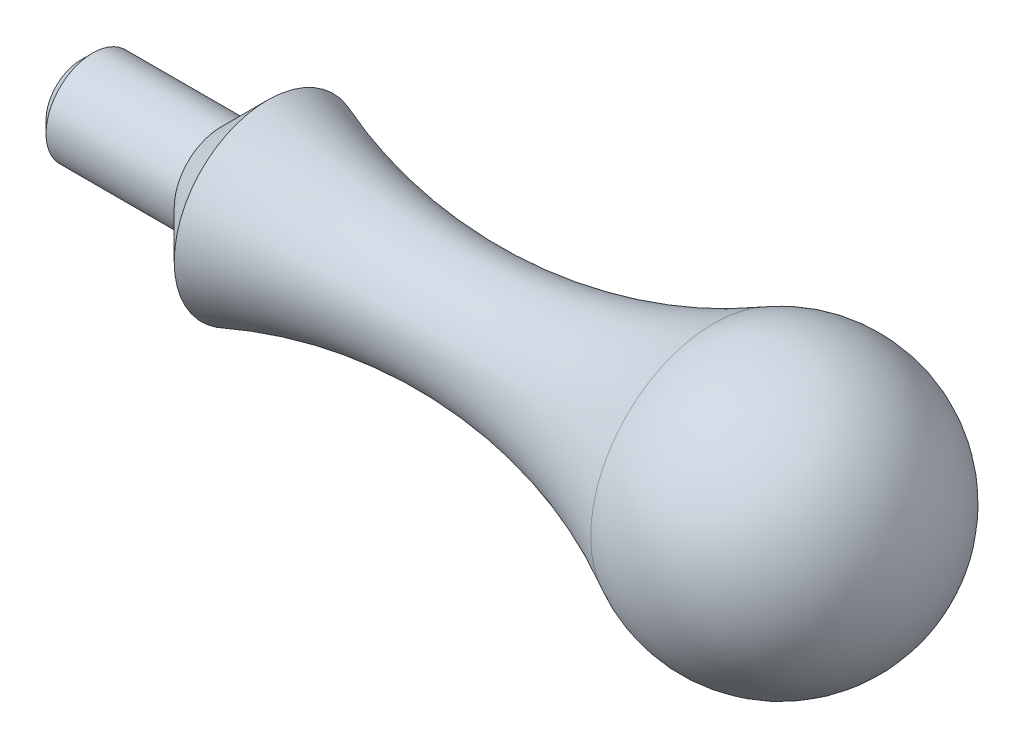
SolidWorks part; units mm, degrees
material "AISI 1015 Steel, Cold Drawn (SS)"
ref_plane "Front" through (0, 0, 0) normal (0, 0, 1) x (1, 0, 0)
ref_plane "Top" through (0, 0, 0) normal (0, 1, 0) x (1, 0, 0)
ref_plane "Right" through (0, 0, 0) normal (1, 0, 0) x (0, 0, -1)
sketch "Sketch1" plane through (0, 0, 0) normal (0, 0, 1) x (1, 0, 0)
  line L0 (-4.0062, 0) -> (65.1899, 0) construction
  line L1 (0, 0) -> (0, 3.175)
  line L2 (0, 3.175) -> (9.525, 3.175)
  line L3 (9.525, 3.175) -> (12.7, 6.35)
  line L4 (0, 0) -> (57.15, 0)
  arc A0 (43.0919, 8.3771) -> (12.7, 6.35) centre (25.6825, 40.5492) cw
  arc A1 (57.15, 0) -> (43.0919, 8.3771) centre (47.625, 0) ccw
  dimension "D3" = 9.525
  dimension "D4" = 12.7
  dimension "D5" = 7.9375
  dimension "D6" = 47.625
  dimension "D1" = 19.05
  dimension "D7" = 45
  dimension "D2" = 6.35
revolve "Revolve1" add sketch "Sketch1" angle 360 about L0
cosmetic thread "Cosmetic Thread1" parameters "D2"=4.8387
chamfer "Chamfer1" distance 0.7937 angle 45 1 edges at (0, 0, 3.175)
